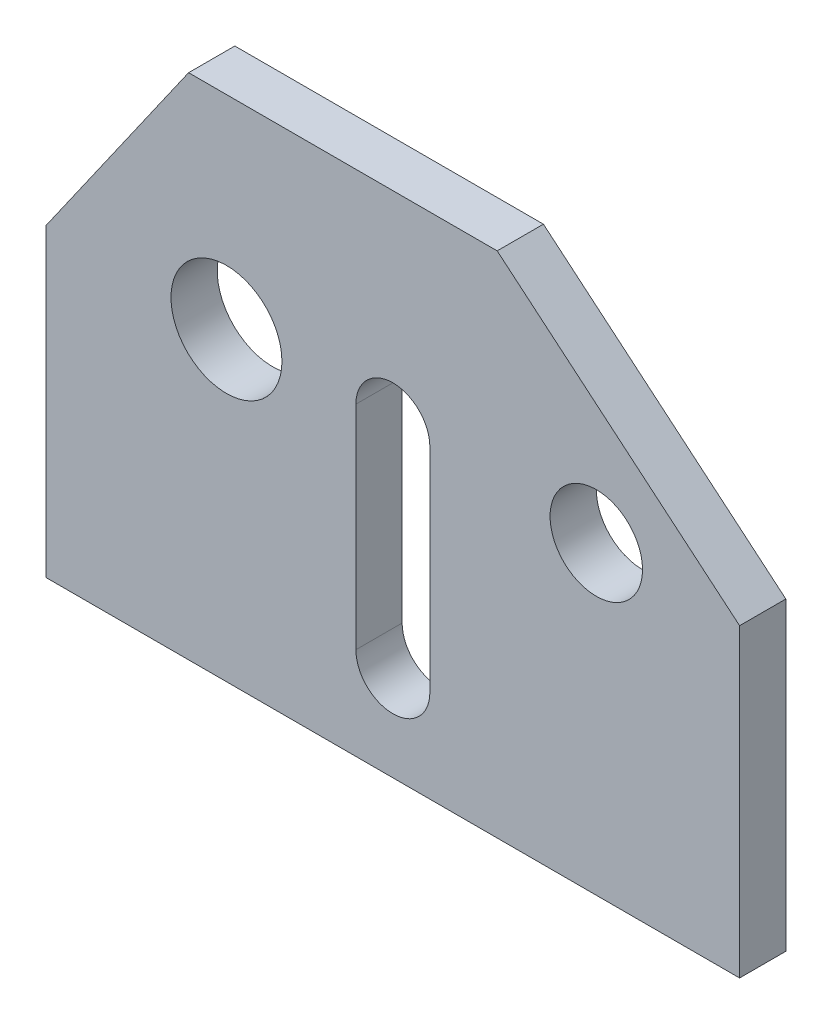
SolidWorks part; units mm, degrees
ref_plane "Front Plane" through (0, 0, 0) normal (0, 0, 1) x (1, 0, 0)
ref_plane "Top Plane" through (0, 0, 0) normal (0, 1, 0) x (1, 0, 0)
ref_plane "Right Plane" through (0, 0, 0) normal (1, 0, 0) x (0, 0, -1)
sketch "Sketch1" plane through (0, 0, 0) normal (0, 0, 1) x (1, 0, 0)
  line L0 (0, 33) -> (0, 58.4222) construction
  line L1 (0, 0) -> (75, 0)
  line L2 (0, 0) -> (0, 33)
  line L4 (75, 0) -> (75, 33)
  line L5 (0, 33) -> (15.4046, 55)
  line L6 (75, 33) -> (75, 62.92) construction
  line L7 (75, 33) -> (48.7814, 55)
  line L8 (48.7814, 55) -> (15.4046, 55)
  line L9 (33.5, 33) -> (33.5, 10)
  line L10 (41.5, 33) -> (41.5, 10)
  line L11 (0, 33) -> (75, 33) construction
  circle A0 centre (19.5, 33) radius 6
  circle A1 centre (59.5, 33) radius 5
  arc A2 (41.5, 33) -> (33.5, 33) centre (37.5, 33) ccw
  arc A3 (33.5, 10) -> (41.5, 10) centre (37.5, 10) ccw
  point P15 (37.5, 33)
  dimension "D6" = 12
  dimension "D7" = 10
  dimension "D8" = 23
  dimension "D9" = 4
  dimension "D1" = 33
  dimension "D2" = 75
  dimension "D3" = 35
  dimension "D4" = 50
  dimension "D5" = 55
  dimension "D10" = 18
  dimension "D11" = 22
extrude "Boss-Extrude1" add sketch "Sketch1" along normal blind 5
